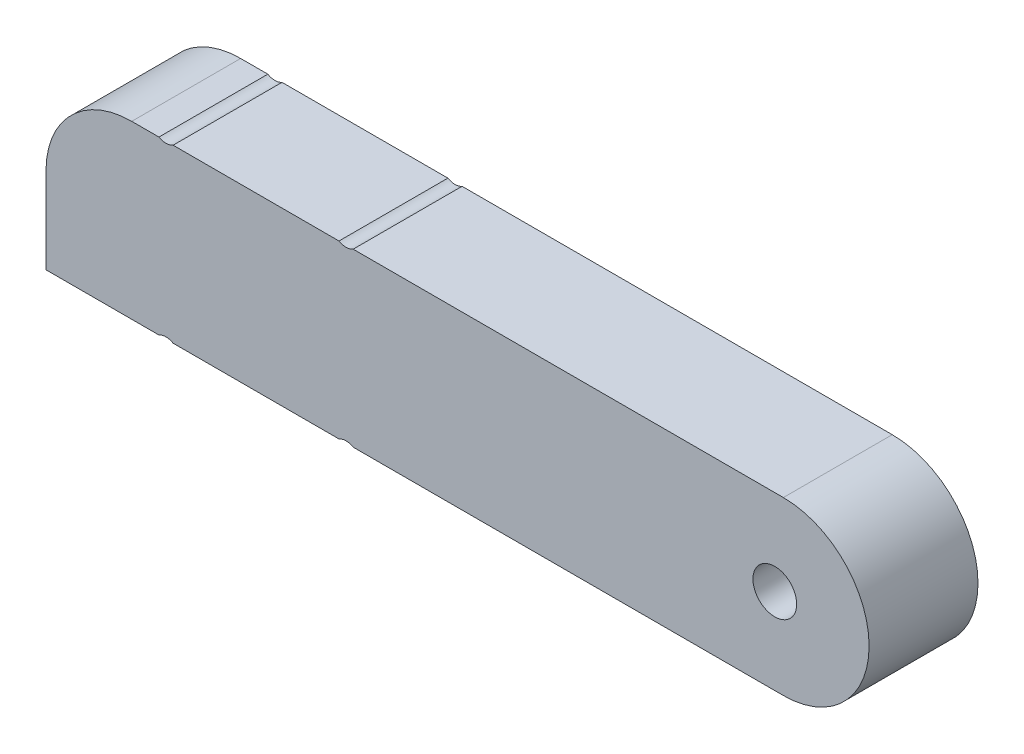
SolidWorks part; units mm, degrees
ref_plane "Front Plane" through (0, 0, 0) normal (0, 0, 1) x (1, 0, 0)
ref_plane "Top Plane" through (0, 0, 0) normal (0, 1, 0) x (1, 0, 0)
ref_plane "Right Plane" through (0, 0, 0) normal (1, 0, 0) x (0, 0, -1)
sketch "Sketch1" plane through (0, 0, 0) normal (0, 0, 1) x (1, 0, 0)
  line L61 (59.7892, 216.6092) -> (59.7892, 206.6092)
  line L62 (59.7892, 206.6092) -> (72.963, 206.6092)
  line L63 (74.6154, 206.6092) -> (93.963, 206.6092)
  line L64 (95.6154, 206.6092) -> (145.7892, 206.6092)
  line L65 (145.7892, 226.6092) -> (95.6154, 226.6092)
  line L66 (93.963, 226.6092) -> (74.6154, 226.6092)
  line L67 (72.963, 226.6092) -> (69.7892, 226.6092)
  arc A63 (69.7892, 226.6092) -> (59.7892, 216.6092) centre (69.7892, 216.6092) ccw
  arc A64 (145.7892, 206.6092) -> (145.7892, 226.6092) centre (145.7892, 216.6092) ccw
  circle A65 centre (144.7892, 216.6092) radius 2.55
  arc A66 (72.963, 226.6092) -> (74.6154, 226.6092) centre (73.7892, 228.0092) ccw
  arc A67 (93.963, 226.6092) -> (95.6154, 226.6092) centre (94.7892, 228.0092) ccw
  arc A68 (95.6154, 206.6092) -> (93.963, 206.6092) centre (94.7892, 205.2092) ccw
  arc A69 (74.6154, 206.6092) -> (72.963, 206.6092) centre (73.7892, 205.2092) ccw
extrude "Boss-Extrude1" add sketch "Sketch1" along normal blind 12.7
